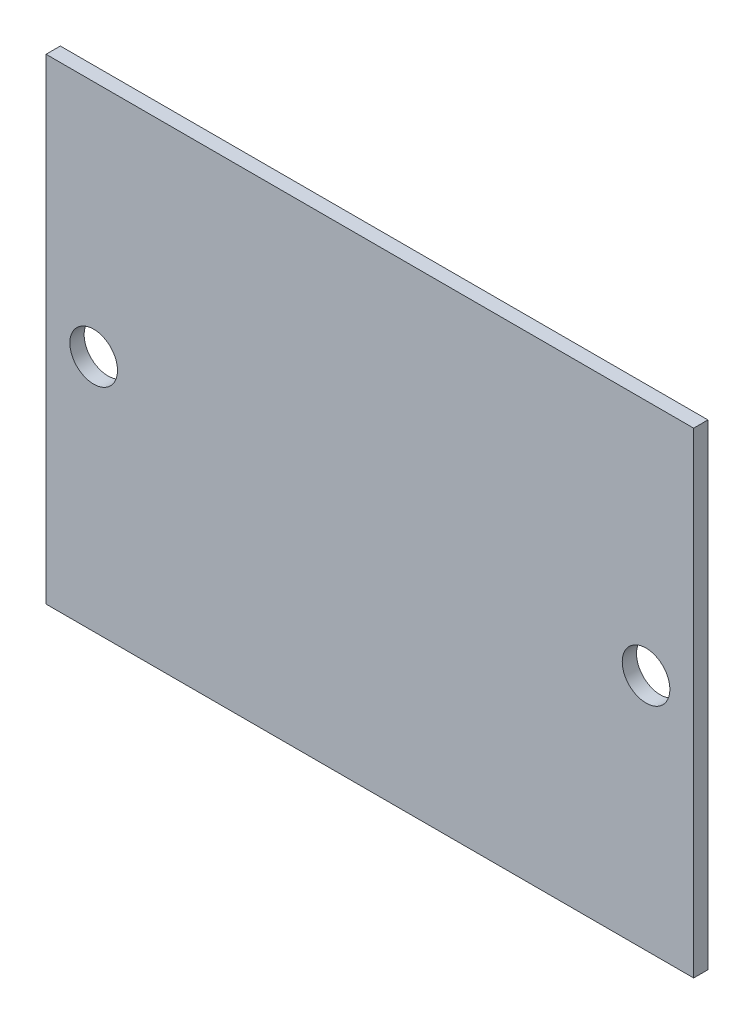
SolidWorks part; units mm, degrees
ref_plane "Front Plane" through (0, 0, 0) normal (0, 0, 1) x (1, 0, 0)
ref_plane "Top Plane" through (0, 0, 0) normal (0, 1, 0) x (1, 0, 0)
ref_plane "Right Plane" through (0, 0, 0) normal (1, 0, 0) x (0, 0, -1)
sketch "ｽｹｯﾁ1" plane through (0, 0, 0) normal (0, 0, 1) x (1, 0, 0)
  line L0 (-29, 0) -> (29, 0) construction
  line L1 (-34, 25) -> (34, 25)
  line L2 (-34, 25) -> (-34, -25)
  line L3 (-34, -25) -> (34, -25)
  line L4 (34, 25) -> (34, -25)
  line L5 (-34, 25) -> (34, -25) construction
  line L6 (-34, -25) -> (34, 25) construction
  line L7 (0, 0) -> (0, 18.3057) construction
  circle A0 centre (-29, 0) radius 2.5
  circle A1 centre (29, 0) radius 2.5
  point P0 (0, 0)
  dimension "D4" = 5
  dimension "D1" = 68
  dimension "D2" = 50
  dimension "D3" = 58
extrude "ﾎﾞｽ - 押し出し1" add sketch "ｽｹｯﾁ1" along normal blind 1.5
